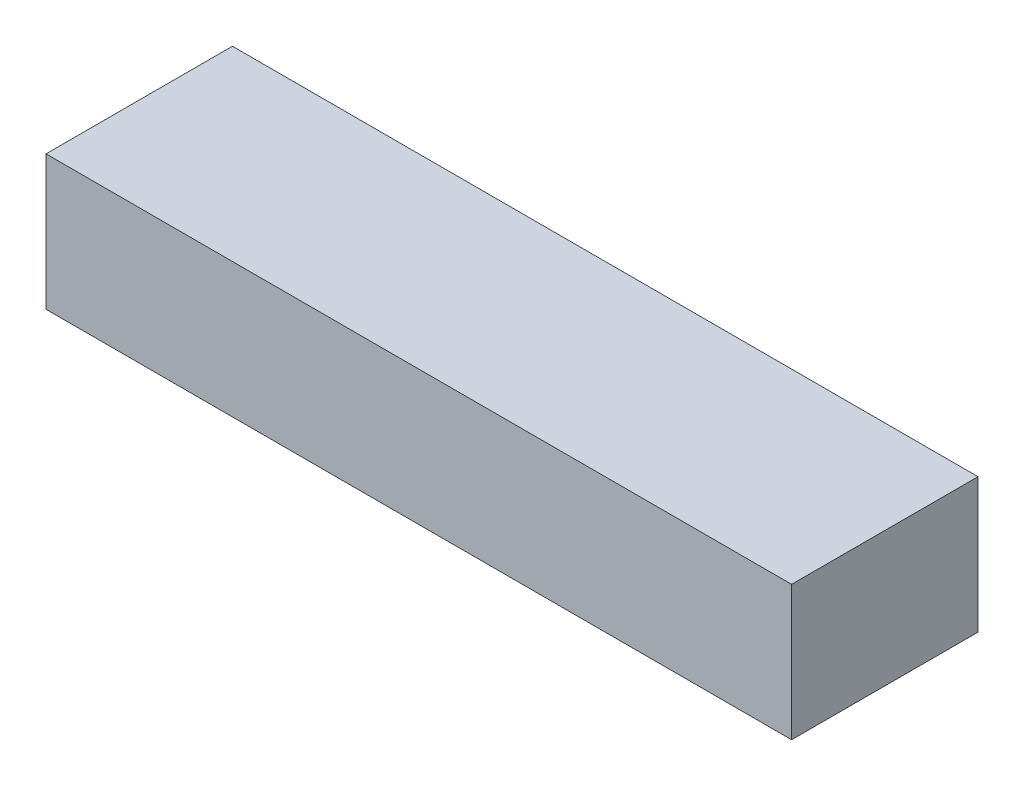
SolidWorks part; units mm, degrees
ref_plane "Ön Düzlem" through (0, 0, 0) normal (0, 0, 1) x (1, 0, 0)
ref_plane "Üst Düzlem" through (0, 0, 0) normal (0, 1, 0) x (1, 0, 0)
ref_plane "Sağ Düzlem" through (0, 0, 0) normal (1, 0, 0) x (0, 0, -1)
sketch "Çizim1" plane through (0, 0, 0) normal (0, 1, 0) x (1, 0, 0)
  line L1 (-54, -13.5) -> (54, -13.5)
  line L2 (-54, -13.5) -> (-54, 13.5)
  line L3 (-54, 13.5) -> (54, 13.5)
  line L4 (54, -13.5) -> (54, 13.5)
  line L5 (-54, -13.5) -> (54, 13.5) construction
  line L6 (-54, 13.5) -> (54, -13.5) construction
  point P0 (0, 0)
  dimension "D1" = 27
  dimension "D2" = 108
extrude "Yükseklik-Ekstrüzyon1" add sketch "Çizim1" along normal blind 19.5
